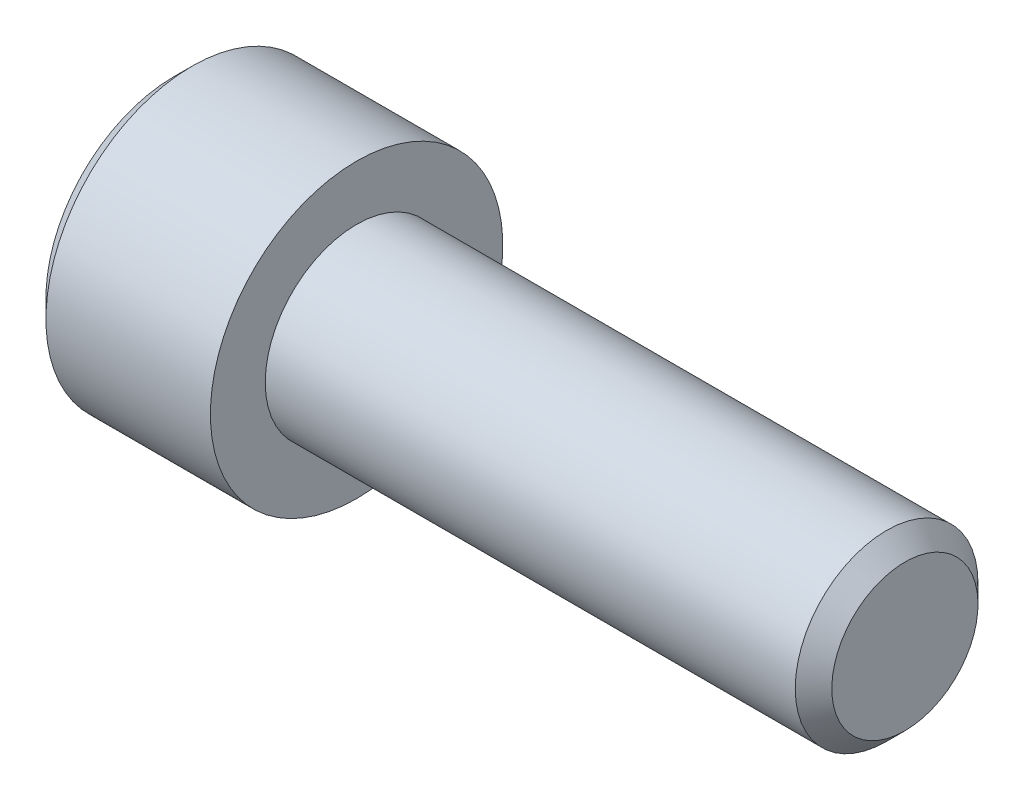
SolidWorks part; units mm, degrees
ref_plane "Front" through (0, 0, 0) normal (0, 0, 1) x (1, 0, 0)
ref_plane "Top" through (0, 0, 0) normal (0, 1, 0) x (1, 0, 0)
ref_plane "Right" through (0, 0, 0) normal (1, 0, 0) x (0, 0, -1)
sketch "Sketch1" plane through (0, 0, 0) normal (0, 0, 1) x (1, 0, 0)
  line L0 (-10, 0) -> (-10, 8)
  line L1 (-10, 0) -> (30, 0)
  line L2 (-10, 8) -> (0, 8)
  line L3 (0, 8) -> (0, 5)
  line L4 (0, 5) -> (30, 5)
  line L6 (30, 5) -> (30, 0)
  line L8 (30, 0) -> (-10, 0) construction
  dimension "D1" = 16
  dimension "D2" = 10
  dimension "D3" = 10
  dimension "D4" = 30
revolve "Revolve1" add sketch "Sketch1" angle 360 about L8
cosmetic thread "Cosmetic Thread1" parameters "D2"=8.619
sketch "Sketch2" plane through (0, 0, 0) normal (0, 0, 1) x (1, 0, 0)
  line L0 (-10, 0) -> (-10, 3.995)
  line L1 (-10, 3.995) -> (-5, 3.995)
  line L2 (-5, 3.995) -> (-3.9295, 0)
  line L3 (-10, 8) -> (-10, -8) construction
  line L4 (-3.9295, 0) -> (-10, 0) construction
  line L5 (-10, 0) -> (-3.9295, 0)
  dimension "D1" = 75
  dimension "D2" = 7.99
  dimension "D3" = 5
revolve "Cut-Revolve1" cut sketch "Sketch2" angle 360 about L4
sketch "Sketch3" plane through (-10, 0, 0) normal (1, 0, 0) x (0, 0, -1)
  line L1 (0, 4.6188) -> (-4, 2.3094)
  line L2 (-4, 2.3094) -> (-4, -2.3094)
  line L3 (-4, -2.3094) -> (0, -4.6188)
  line L4 (0, -4.6188) -> (4, -2.3094)
  line L5 (4, -2.3094) -> (4, 2.3094)
  line L6 (4, 2.3094) -> (0, 4.6188)
  circle A0 centre (0, 0) radius 4 construction
  dimension "D1" = 8
extrude "Cut-Extrude1" cut sketch "Sketch3" along normal blind 5
chamfer "Chamfer1" distance 1 angle 45 2 edges at (-10, -8, 0) (30, -5, 0)
